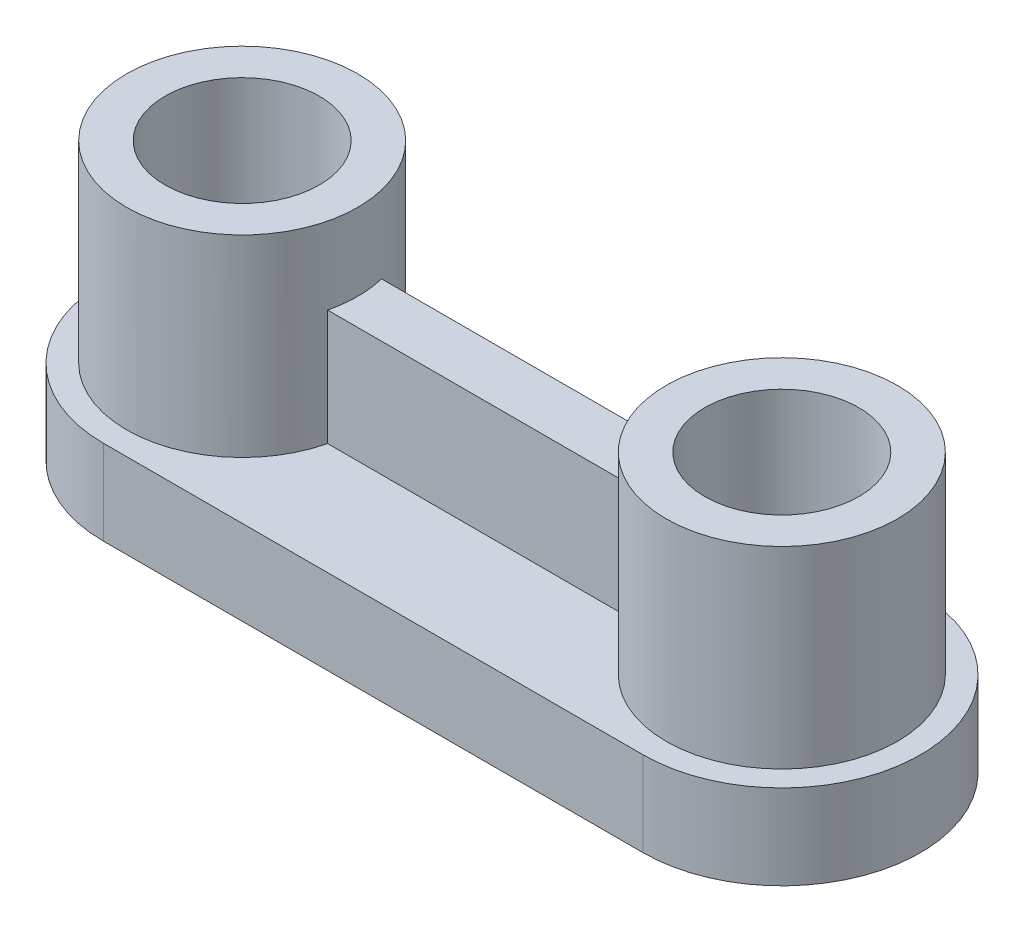
SolidWorks part; units mm, degrees
ref_plane "Front Plane" through (0, 0, 0) normal (0, 0, 1) x (1, 0, 0)
ref_plane "Top Plane" through (0, 0, 0) normal (0, 1, 0) x (1, 0, 0)
ref_plane "Right Plane" through (0, 0, 0) normal (1, 0, 0) x (0, 0, -1)
sketch "Sketch1" plane through (0, 0, 0) normal (0, 1, 0) x (1, 0, 0)
  line L0 (0, 0) -> (70, 0) construction
  line L1 (0, 18) -> (70, 18)
  line L2 (0, -18) -> (70, -18)
  arc A0 (0, 18) -> (0, -18) centre (0, 0) ccw
  arc A1 (70, -18) -> (70, 18) centre (70, 0) ccw
  point P3 (35, 0)
  dimension "L_Base" = 70
  dimension "D2" = 36
extrude "Boss-Extrude1" add sketch "Sketch1" along normal blind 11
sketch "Sketch2" plane through (0, 11, 0) normal (0, 1, 0) x (1, 0, 0)
  circle A0 centre (0, 0) radius 15
  circle A1 centre (70, 0) radius 15
  dimension "D1" = 30
  dimension "D2" = 30
extrude "Boss-Extrude2" add sketch "Sketch2" along normal blind 25
sketch "Sketch5" plane through (0, 36, 0) normal (0, 1, 0) x (1, 0, 0)
  line L0 (0, 0) -> (70, 0)
  circle A0 centre (70, 0) radius 10
  circle A1 centre (0, 0) radius 10
  dimension "D1" = 20
  dimension "D2" = 20
extrude "Cut-Extrude1" cut sketch "Sketch5" against normal blind 20 contours A1 | A0
sketch "Sketch8" plane through (0, 16, 0) normal (0, 1, 0) x (1, 0, 0)
  circle A0 centre (0, 0) radius 7.5
  circle A1 centre (70, 0) radius 7.5
  dimension "D1" = 15
  dimension "D2" = 15
extrude "Cut-Extrude2" cut sketch "Sketch8" against normal through all contours A0
sketch "Sketch13" plane through (0, 16, 0) normal (0, 1, 0) x (1, 0, 0)
  circle A0 centre (70, 0) radius 7.5
  dimension "D1" = 15
extrude "Cut-Extrude3" cut sketch "Sketch13" against normal through all contours A0
sketch "Sketch14" plane through (0, 0, 0) normal (0, -1, 0) x (1, 0, 0)
  line L1 (17, 9.9538) -> (53, 9.9538)
  line L2 (17, 9.9538) -> (17, -10.0462)
  line L3 (17, -10.0462) -> (53, -10.0462)
  line L4 (53, 9.9538) -> (53, -10.0462)
  line L5 (17, 9.9538) -> (53, -10.0462) construction
  line L6 (17, -10.0462) -> (53, 9.9538) construction
  point P0 (35, -0.0462)
  dimension "D1" = 36
  dimension "D2" = 20
  dimension "D3" = 35
extrude "Cut-Extrude4" cut sketch "Sketch14" against normal blind 5 contours L2 L1 L4 L3
sketch "Sketch18" plane through (0, 11, 0) normal (0, 1, 0) x (1, 0, 0)
  line L0 (15, 0) -> (35, 0)
  line L1 (55, 0) -> (35, 0)
  line L3 (55.455, -3.5) -> (14.545, -3.5)
  line L4 (55.455, -3.5) -> (55.455, 3.5)
  line L5 (55.455, 3.5) -> (14.545, 3.5)
  line L6 (14.545, -3.5) -> (14.545, 3.5)
  line L7 (55.455, -3.5) -> (14.545, 3.5) construction
  line L8 (55.455, 3.5) -> (14.545, -3.5) construction
  circle A0 centre (0, 0) radius 15 construction
  circle A1 centre (0, 0) radius 15 construction
  circle A2 centre (70, 0) radius 15 construction
  circle A3 centre (70, 0) radius 15 construction
  dimension "D1" = 40.91
  dimension "D2" = 7
extrude "Boss-Extrude5" add sketch "Sketch18" along normal blind 15 contours L4 L3 L6 L5
